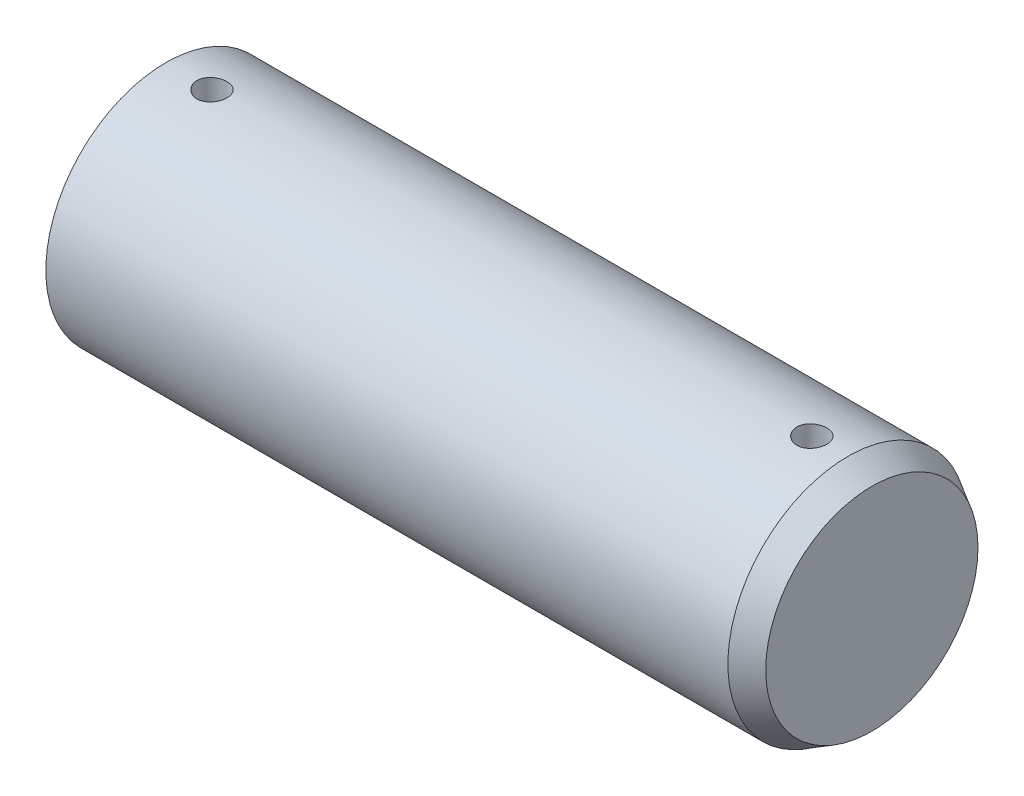
SolidWorks part; units mm, degrees
ref_plane "Front" through (0, 0, 0) normal (0, 0, 1) x (1, 0, 0)
ref_plane "Top" through (0, 0, 0) normal (0, 1, 0) x (1, 0, 0)
ref_plane "Right" through (0, 0, 0) normal (1, 0, 0) x (0, 0, -1)
sketch "Sketch2" plane through (0, 0, 0) normal (1, 0, 0) x (0, 0, -1)
  circle A0 centre (0, 0) radius 12.7
  dimension "D1" = 25.4
extrude "Boss-Extrude1" add sketch "Sketch2" along normal blind 76.2
chamfer "Chamfer1" distance 2.54 angle 30 2 edges at (76.2, 0, -12.7) (0, 0, -12.7)
sketch "Sketch6" plane through (0, 0, 0) normal (0, 1, 0) x (1, 0, 0)
  line L0 (0, 0) -> (6.35, 0) construction
  line L1 (6.35, 0) -> (69.85, 0) construction
  circle A0 centre (6.35, 0) radius 1.5875
  circle A1 centre (69.85, 0) radius 1.5875
  dimension "D3" = 3.175
  dimension "D1" = 6.35
  dimension "D2" = 63.5
extrude "Cut-Extrude1" cut sketch "Sketch6" against normal through all both and the other way through all
